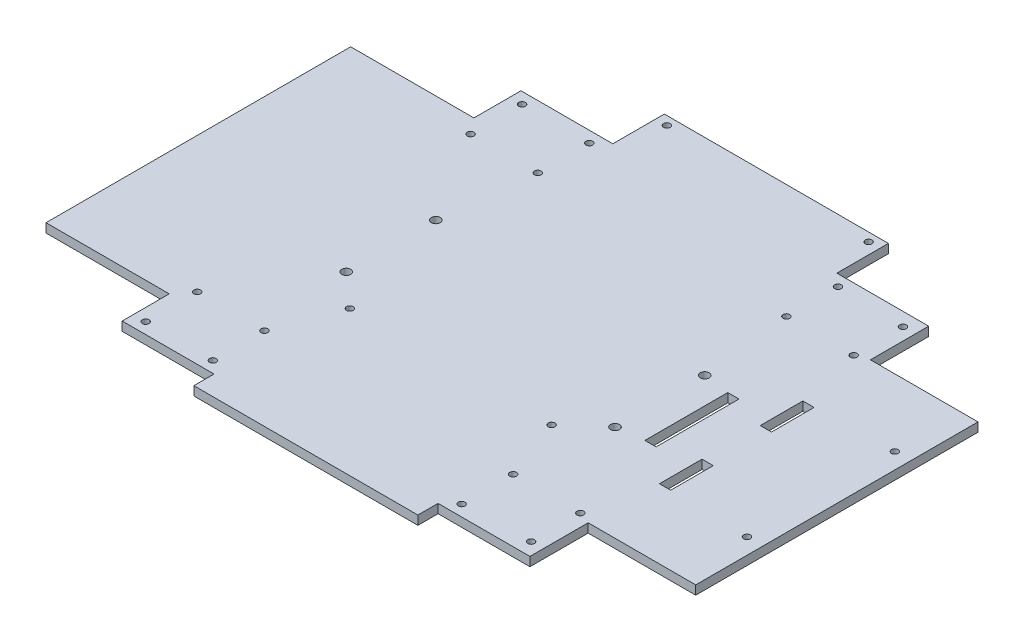
SolidWorks part; units mm, degrees
ref_plane "前视基准面" through (0, 0, 0) normal (0, 0, 1) x (1, 0, 0)
ref_plane "上视基准面" through (0, 0, 0) normal (0, 1, 0) x (1, 0, 0)
ref_plane "右视基准面" through (0, 0, 0) normal (1, 0, 0) x (0, 0, -1)
sketch "草图1" plane through (0, 0, 0) normal (0, 1, 0) x (1, 0, 0)
  line L0 (0, 0) -> (300, 0) construction
  line L1 (0, 0) -> (28, 0) construction
  line L2 (290, -63) -> (290, 63)
  line L4 (28, 0) -> (290, 0) construction
  line L13 (101, 7) -> (101, 112) construction
  line L14 (101, 112) -> (201, 112)
  line L16 (101, 7) -> (101, -98) construction
  line L17 (101, -98) -> (201, -98)
  line L25 (242, 63) -> (290, 63)
  line L26 (242, -63) -> (290, -63)
  line L28 (60, 68) -> (5, 68)
  line L29 (60, -68) -> (5, -68)
  line L34 (60, 68) -> (60, 89)
  line L35 (60, -68) -> (60, -89)
  line L36 (60, 89) -> (101, 89)
  line L37 (60, -89) -> (101, -89)
  line L38 (101, 89) -> (101, 112)
  line L40 (201, 112) -> (201, 89)
  line L41 (201, 89) -> (242, 89)
  line L42 (242, 89) -> (242, 63)
  line L43 (201, -98) -> (201, -89)
  line L44 (201, -89) -> (242, -89)
  line L45 (242, -89) -> (242, -63)
  line L46 (101, -89) -> (101, -98)
  line L48 (5, 68) -> (5, -68)
extrude "底盘" add sketch "草图1" along normal mid plane 4
sketch "草图5" plane through (0, 0, 0) normal (0, 1, 0) x (1, 0, 0)
  line L0 (101, 89) -> (101, 61) construction
  line L1 (101, 61) -> (95.5, 61) construction
  line L2 (95.5, 61) -> (65.5, 61)
  line L3 (65.5, 61) -> (65.5, 84)
  line L4 (95.5, 61) -> (95.5, 84)
  line L5 (242, 89) -> (236.5, 89) construction
  line L7 (236.5, 89) -> (236.5, 61) construction
  line L8 (236.5, 61) -> (206.5, 61)
  line L9 (206.5, 61) -> (206.5, 84)
  line L10 (236.5, 61) -> (236.5, 83)
  line L11 (-283.1027, 0) -> (339.1027, 0) construction
  line L12 (242, 89) -> (201, 89) construction
  circle A0 centre (65.5, 84) radius 1.5
  circle A1 centre (95.5, 84) radius 1.5
  circle A2 centre (65.5, 61) radius 1.5
  circle A3 centre (95.5, 61) radius 1.5
  circle A4 centre (206.5, 61) radius 1.5
  circle A5 centre (206.5, 84) radius 1.5
  circle A6 centre (236.5, 61) radius 1.5
  circle A7 centre (236.5, 83) radius 1.5
  circle A8 centre (236.5, -61) radius 1.5
  circle A9 centre (206.5, -61) radius 1.5
  circle A10 centre (236.5, -83) radius 1.5
  circle A11 centre (206.5, -84) radius 1.5
  circle A12 centre (95.5, -61) radius 1.5
  circle A13 centre (95.5, -84) radius 1.5
  circle A14 centre (65.5, -61) radius 1.5
  circle A15 centre (65.5, -84) radius 1.5
  point P27 (28, 0)
extrude "电机固定孔" cut sketch "草图5" against normal through all both and the other way through all contours A0 | A1 | A2 | A3 | A5 | A7 | A6 | A4 | A14 | A15 | A12 | A13 | A9 | A11 | A8 | A10
sketch "GB37" plane through (0, 0, 0) normal (0, 1, 0) x (1, 0, 0)
  point P13 (28, 0)
sketch "麦轮" plane through (0, 0, 0) normal (0, 1, 0) x (1, 0, 0)
  line L11 (-284.9072, 0) -> (340.9072, 0) construction
  point P18 (28, 0)
sketch "电路板" plane through (0, 0, 0) normal (0, 1, 0) x (1, 0, 0)
sketch "草图10" plane through (0, 0, 0) normal (0, 1, 0) x (1, 0, 0)
  line L1 (196, -33.34) -> (106, -33.34)
  line L2 (196, -33.34) -> (196, 108.16)
  line L3 (196, 108.16) -> (106, 108.16)
  line L4 (106, -33.34) -> (106, 108.16)
  line L5 (151, 108.16) -> (151, -33.34) construction
  line L6 (196, 37.41) -> (106, 37.41) construction
  circle A0 centre (106, 108.16) radius 1.5
  circle A1 centre (196, 108.16) radius 1.5
  circle A2 centre (106, -33.34) radius 1.5
  circle A3 centre (196, -33.34) radius 1.5
  point P0 (151, 37.41)
  point P8 (151, 37.41)
extrude "电路板固定孔" cut sketch "草图10" against normal through all both and the other way through all contours A0 | A1 | A2 | A3
sketch "草图11" plane through (0, 0, 0) normal (0, 1, 0) x (1, 0, 0)
  line L0 (101, 0) -> (151, 0)
  line L1 (-284.9072, 0) -> (340.9072, 0) construction
  line L3 (151, 0) -> (91, 0)
  line L4 (151, 0) -> (211, 0)
  line L5 (91, 0) -> (91, 20)
  line L6 (91, 0) -> (91, -20)
  line L7 (211, 0) -> (211, 20)
  line L8 (211, 0) -> (211, -20)
  circle A0 centre (91, 20) radius 2
  circle A1 centre (91, -20) radius 2
  circle A2 centre (211, 20) radius 2
  circle A3 centre (211, -20) radius 2
extrude "上下底板连接孔" cut sketch "草图11" against normal through all both and the other way through all contours A0 | A1 | A3 | A2
sketch "草图12" plane through (0, 0, 0) normal (0, 1, 0) x (1, 0, 0)
  line L0 (289.8215, 0) -> (247.8215, 0) construction
  line L1 (-284.9072, 0) -> (340.9072, 0) construction
  line L2 (262.8215, 0) -> (227.8215, 0) construction
  line L3 (247.8215, 13) -> (242.8215, 13)
  line L4 (247.8215, 0) -> (247.8215, 13) construction
  line L5 (247.8215, 0) -> (247.8215, -13) construction
  line L6 (227.8215, 0) -> (227.8215, 18.5) construction
  line L7 (242.8215, -13) -> (247.8215, -13)
  line L8 (289.8215, 0) -> (267.8215, 0)
  line L17 (267.8215, 0) -> (267.8215, 18.5)
  line L18 (267.8215, 0) -> (265.3215, 0)
  line L19 (247.8215, 13) -> (247.8215, 32)
  line L20 (262.8215, -18.5) -> (267.8215, -18.5)
  line L21 (262.8215, -18.5) -> (262.8215, 18.5)
  line L22 (262.8215, 18.5) -> (267.8215, 18.5)
  line L23 (267.8215, -18.5) -> (267.8215, 18.5)
  line L24 (265.3215, 18.5) -> (265.3215, -18.5) construction
  line L25 (262.8215, 0) -> (267.8215, 0) construction
  line L26 (242.8215, -13) -> (242.8215, -32)
  line L27 (242.8215, -32) -> (247.8215, -32)
  line L28 (247.8215, 32) -> (242.8215, 32)
  line L33 (247.8215, -13) -> (247.8215, -32)
  line L34 (227.8215, 18.5) -> (222.8215, 18.5) construction
  line L35 (242.8215, 13) -> (242.8215, 32)
  line L37 (227.8215, 18.5) -> (222.8215, 18.5)
  line L38 (227.8215, 18.5) -> (227.8215, -18.5)
  line L39 (227.8215, -18.5) -> (222.8215, -18.5)
  line L40 (222.8215, 18.5) -> (222.8215, -18.5)
extrude "红外线孔" cut sketch "草图12" against normal through all both and the other way through all contours L3 L35 L28 L19 | L7 L33 L27 L26 | L38 L39 L40 L37
sketch "草图13" plane through (0, 0, 0) normal (0, 1, 0) x (1, 0, 0)
  line L0 (289.8811, 0) -> (282.3811, 0)
  line L1 (-284.9072, 0) -> (340.9072, 0) construction
  line L2 (282.3811, 0) -> (280.8811, 0)
  line L3 (280.8811, 0) -> (284.8811, 0)
  line L4 (282.8811, 0) -> (282.8811, 33)
  line L5 (282.8811, 0) -> (282.8811, -33)
  circle A0 centre (282.8811, 33) radius 1.5
  circle A1 centre (282.8811, -33) radius 1.5
extrude "红外固定孔" cut sketch "草图13" against normal through all both and the other way through all contours A0 | A1
